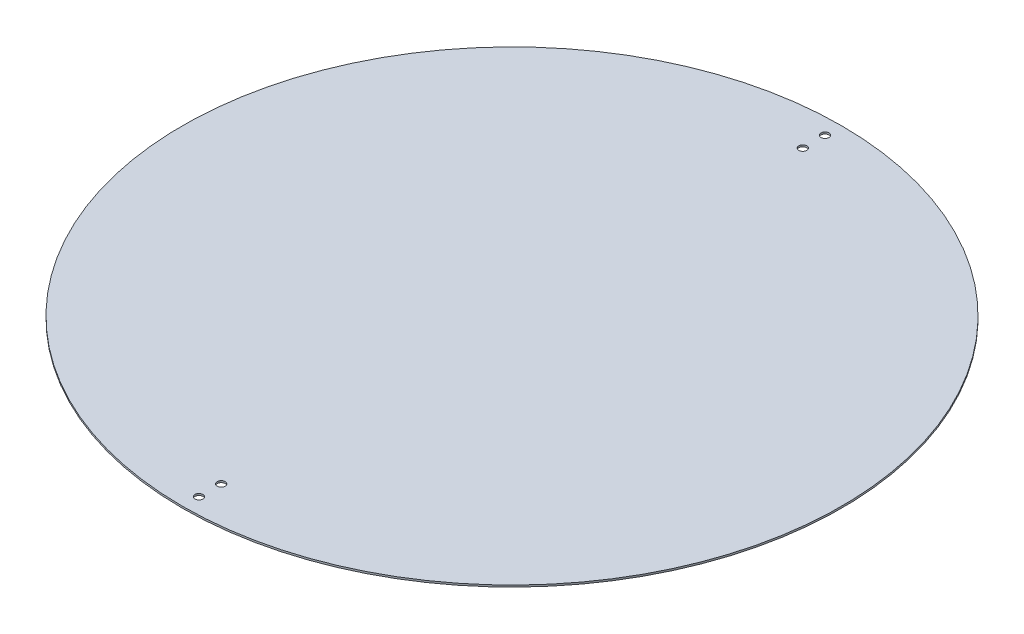
SolidWorks part; units mm, degrees
material "Galvanized Steel"
ref_plane "Front Plane" through (0, 0, 0) normal (0, 0, 1) x (1, 0, 0)
ref_plane "Top Plane" through (0, 0, 0) normal (0, 1, 0) x (1, 0, 0)
ref_plane "Right Plane" through (0, 0, 0) normal (1, 0, 0) x (0, 0, -1)
sketch "Sketch1" plane through (0, 0, 0) normal (0, 1, 0) x (1, 0, 0)
  circle A0 centre (0, 0) radius 370
  dimension "D1" = 740
extrude "Boss-Extrude1" add sketch "Sketch1" along normal mid plane 2
sketch "Sketch2" plane through (0, 1, 0) normal (0, 1, 0) x (1, 0, 0)
  line L0 (0, 494.6747) -> (0, -426.1264) construction
  circle A0 centre (0, -326.5) radius 4.5 construction
  circle A2 centre (0, -351.5) radius 4.5 construction
  circle A3 centre (0, 351.5) radius 4.5 construction
  circle A4 centre (0, 326.5) radius 4.5 construction
  circle A8 centre (0, -351.5) radius 4.5
  circle A9 centre (0, -326.5) radius 4.5
  circle A10 centre (0, 326.5) radius 4.5
  circle A11 centre (0, 351.5) radius 4.5
  circle A12 centre (0, 0) radius 370 construction
  point P13 (0, -351.5)
  point P14 (0, -326.5)
  point P15 (0, 351.5)
  point P16 (0, 326.5)
  dimension "D1" = 9
  dimension "D2" = 9
  dimension "D3" = 9
  dimension "D5" = 18.5
  dimension "D6" = 326.5
  dimension "D7" = 18.5
  dimension "D8" = 9
  dimension "D4" = 326.5
extrude "Cut-Extrude1" cut sketch "Sketch2" against normal up to next
